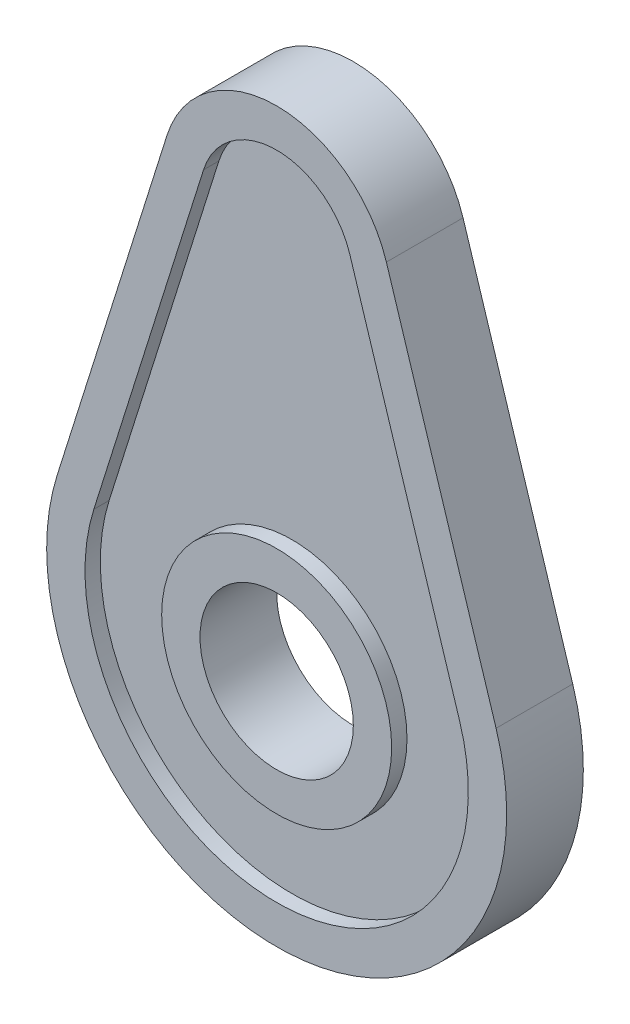
SolidWorks part; units mm, degrees
ref_plane "Front Plane" through (0, 0, 0) normal (0, 0, 1) x (1, 0, 0)
ref_plane "Top Plane" through (0, 0, 0) normal (0, 1, 0) x (1, 0, 0)
ref_plane "Right Plane" through (0, 0, 0) normal (1, 0, 0) x (0, 0, -1)
sketch "Sketch1" plane through (0, 0, 0) normal (0, 0, 1) x (1, 0, 0)
  line L0 (-14.3091, 54.5) -> (-28.6182, 9)
  line L1 (0, 84.7852) -> (0, -62.2973) construction
  line L2 (14.3091, 54.5) -> (28.6182, 9)
  arc A0 (-28.6182, 9) -> (28.6182, 9) centre (0, 0) ccw
  circle A1 centre (0, 0) radius 10
  arc A2 (14.3091, 54.5) -> (-14.3091, 54.5) centre (0, 50) ccw
  dimension "D1" = 60
  dimension "D2" = 20
  dimension "D3" = 30
  dimension "D4" = 50
extrude "Boss-Extrude1" add sketch "Sketch1" along normal blind 10
sketch "Sketch2" plane through (0, 0, 10) normal (0, 0, 1) x (1, 0, 0)
  line L4 (23.8485, 7.5) -> (9.5394, 53)
  line L5 (-9.5394, 53) -> (-23.8485, 7.5)
  line L6 (23.8485, 7.5) -> (9.5394, 53)
  line L7 (-9.5394, 53) -> (-23.8485, 7.5)
  arc A4 (-23.8485, 7.5) -> (23.8485, 7.5) centre (0, 0) ccw
  arc A5 (9.5394, 53) -> (-9.5394, 53) centre (0, 50) ccw
  arc A6 (-23.8485, 7.5) -> (23.8485, 7.5) centre (0, 0) ccw
  arc A7 (9.5394, 53) -> (-9.5394, 53) centre (0, 50) ccw
  circle A8 centre (0, 0) radius 15
  circle A9 centre (0, 0) radius 15
  dimension "D1" = 5
  dimension "D2" = 5
extrude "Cut-Extrude1" cut sketch "Sketch2" against normal blind 2
ref_plane "Plane1" through (0, 0, 5) normal (0, 0, 1) x (1, 0, 0)
mirror "Mirror1" about plane through (0, 0, 5) normal (0, 0, 1) of "Cut-Extrude1"
